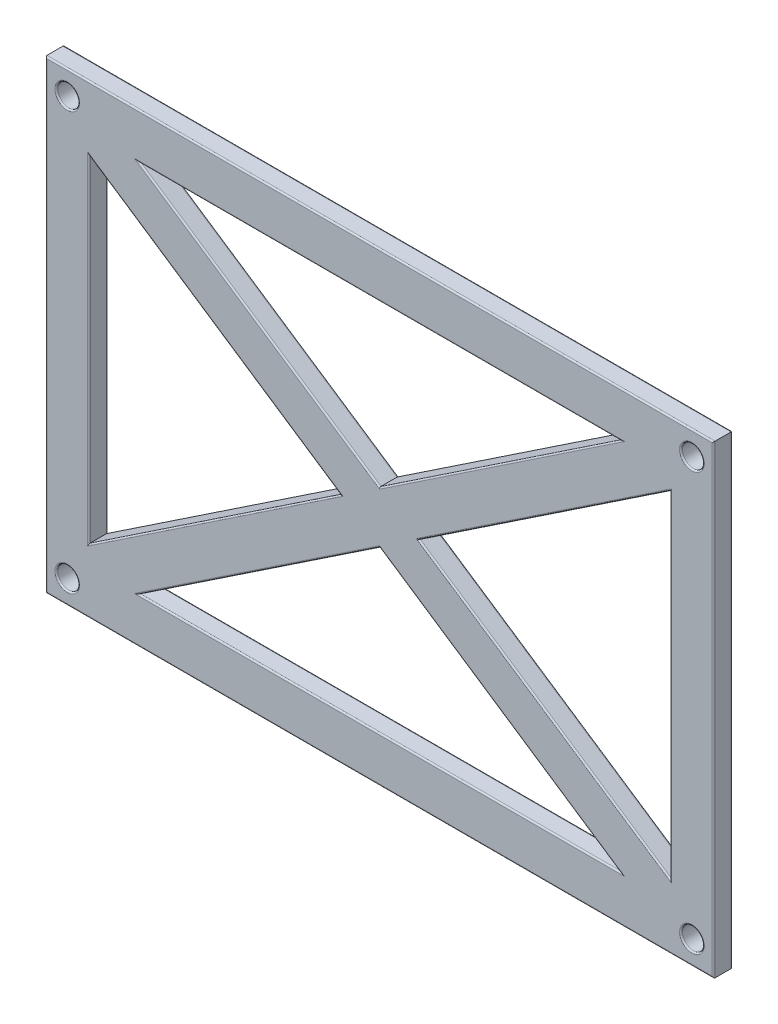
SolidWorks part; units mm, degrees
ref_plane "前视基准面" through (0, 0, 0) normal (0, 0, 1) x (1, 0, 0)
ref_plane "上视基准面" through (0, 0, 0) normal (0, 1, 0) x (1, 0, 0)
ref_plane "右视基准面" through (0, 0, 0) normal (1, 0, 0) x (0, 0, -1)
other "Configuration Table"
sketch "草图1" plane through (0, 0, 0) normal (0, 0, 1) x (1, 0, 0)
  line L0 (-43, 0) -> (43, 0) construction
  line L1 (-43, 28.75) -> (43, 28.75) construction
  line L2 (-43, 28.75) -> (-43, -28.75) construction
  line L3 (-43, -28.75) -> (43, -28.75) construction
  line L4 (43, 28.75) -> (43, -28.75) construction
  line L5 (-43, 28.75) -> (43, -28.75) construction
  line L6 (-43, -28.75) -> (43, 28.75) construction
  line L7 (0, 28.75) -> (0, -28.75) construction
  line L9 (-46, 32) -> (46, 32)
  line L10 (-46, 32) -> (-46, -32)
  line L11 (-46, -32) -> (46, -32)
  line L12 (46, 32) -> (46, -32)
  line L13 (-46, 32) -> (46, -32) construction
  line L14 (-46, -32) -> (46, 32) construction
  circle A0 centre (-43, 28.75) radius 1.5
  circle A1 centre (43, 28.75) radius 1.5
  circle A2 centre (-43, -28.75) radius 1.5
  circle A3 centre (43, -28.75) radius 1.5
  point P0 (0, 0)
  point P9 (0, 0)
  point P12 (0, 0)
  point P16 (0, 0)
  dimension "D3" = 92
  dimension "D1" = 86
  dimension "D2" = 57.5
  dimension "D4" = 64
extrude "凸台-拉伸1" add sketch "草图1" along normal blind 2.6
sketch "草图2" plane through (0, 0, 2.6) normal (0, 0, 1) x (1, 0, 0)
  line L0 (-43, 28.75) -> (0, 0)
  line L1 (0, 0) -> (43, 28.75)
  line L2 (43, 28.75) -> (43, -28.75)
  line L3 (43, -28.75) -> (0, 0)
  line L4 (0, 0) -> (-43, -28.75)
  line L5 (-43, -28.75) -> (43, -28.75)
  line L6 (-43, 28.75) -> (-43, -28.75)
  line L7 (-43, 28.75) -> (43, 28.75)
  line L8 (-46, 28.75) -> (-46, -28.75)
  line L9 (-1.6674, 2.4939) -> (-44.6674, -26.2561)
  line L10 (-43, -31.75) -> (43, -31.75)
  line L11 (44.6674, -26.2561) -> (1.6674, 2.4939)
  line L12 (1.6674, -2.4939) -> (44.6674, 26.2561)
  line L13 (40, 28.75) -> (40, -28.75)
  line L14 (-44.6674, 26.2561) -> (-1.6674, -2.4939)
  line L15 (-43, 25.75) -> (43, 25.75)
  line L16 (-40, 28.75) -> (-40, -28.75)
  line L17 (1.6674, -2.4939) -> (-41.3326, -31.2439)
  line L18 (-43, -25.75) -> (43, -25.75)
  line L19 (41.3326, -31.2439) -> (-1.6674, -2.4939)
  line L20 (-1.6674, 2.4939) -> (41.3326, 31.2439)
  line L21 (46, 28.75) -> (46, -28.75)
  line L22 (-41.3326, 31.2439) -> (1.6674, 2.4939)
  line L23 (-43, 31.75) -> (43, 31.75)
  circle A0 centre (-43, -28.75) radius 1.5 construction
  circle A1 centre (43, -28.75) radius 1.5 construction
  circle A2 centre (43, 28.75) radius 1.5 construction
  circle A3 centre (-43, 28.75) radius 1.5 construction
  circle A4 centre (-43, -28.75) radius 1.5
  circle A5 centre (43, -28.75) radius 1.5
  circle A6 centre (43, 28.75) radius 1.5
  circle A7 centre (-43, 28.75) radius 1.5
  circle A8 centre (-43, 28.75) radius 3.5
  circle A9 centre (43, 28.75) radius 3.5
  circle A10 centre (43, -28.75) radius 3.5
  circle A11 centre (-43, -28.75) radius 3.5
  dimension "D2" = 3
  dimension "D1" = 2
  dimension "D3" = 3
extrude "切除-拉伸1" cut sketch "草图2" against normal blind 2.6 contours L15 L22 L20 | L18 L19 L17 | L13 L12 L11 | L14 L16 L9
fillet "圆角1" radius 0.2 40 edges at (22.6987, -11.5677, 2.6) (40, 0, 2.6) (22.6987, 11.5677, 2.6) (-22.6987, -11.5677, 2.6) (-22.6987, 11.5677, 2.6) (-40, 0, 2.6) (16.5578, 14.6794, 2.6) (0, 25.75, 2.6) (-16.5578, 14.6794, 2.6) (44.5, -28.75, 2.6) (44.5, 28.75, 2.6) (0, -32, 2.6) (-46, 0, 2.6) (0, 32, 2.6) (46, 0, 2.6) (-41.5, 28.75, 2.6) (-41.5, -28.75, 2.6) (16.5578, -14.6794, 2.6) (-16.5578, -14.6794, 2.6) (0, -25.75, 2.6) (22.6987, -11.5677, 0) (22.6987, 11.5677, 0) (40, 0, 0) (16.5578, -14.6794, 0) (0, -25.75, 0) (-16.5578, -14.6794, 0) (16.5578, 14.6794, 0) (-16.5578, 14.6794, 0) (0, 25.75, 0) (0, 32, 0) (-46, 0, 0) (0, -32, 0) (46, 0, 0) (-41.5, 28.75, 0) (44.5, 28.75, 0) (-41.5, -28.75, 0) (44.5, -28.75, 0) (-22.6987, -11.5677, 0) (-40, 0, 0) (-22.6987, 11.5677, 0)
